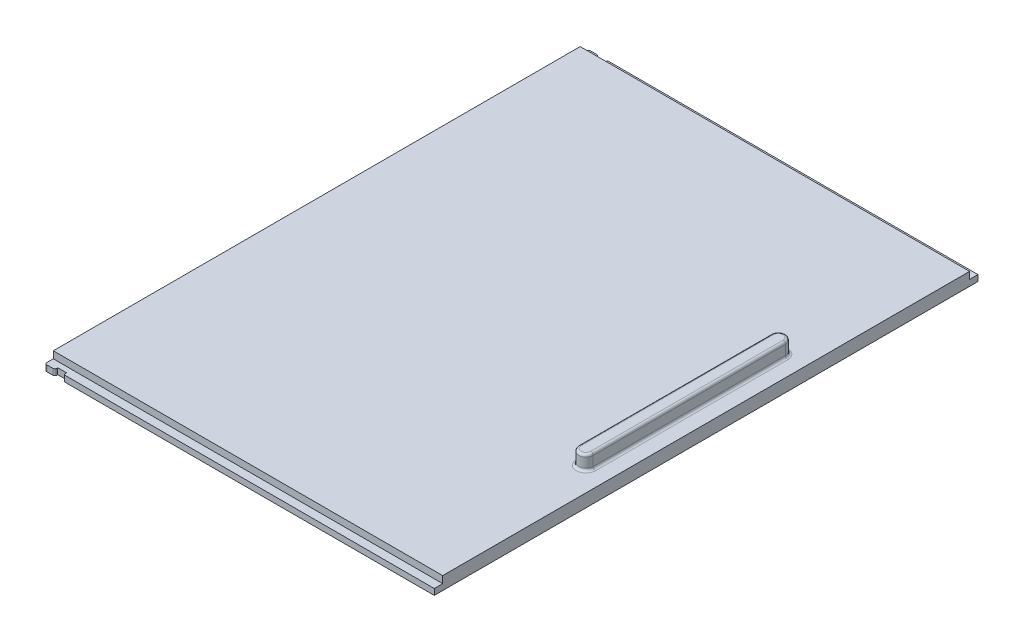
SolidWorks part; units mm, degrees
ref_plane "Front Plane" through (0, 0, 0) normal (0, 0, 1) x (1, 0, 0)
ref_plane "Top Plane" through (0, 0, 0) normal (0, 1, 0) x (1, 0, 0)
ref_plane "Right Plane" through (0, 0, 0) normal (1, 0, 0) x (0, 0, -1)
sketch "Sketch1" plane through (0, 0, 0) normal (0, 1, 0) x (1, 0, 0)
  line L1 (0, 0) -> (81, 0)
  line L2 (0, 0) -> (0, 116)
  line L3 (0, 116) -> (81, 116)
  line L4 (81, 0) -> (81, 116)
  dimension "D1" = 116
  dimension "D2" = 81
extrude "Boss-Extrude1" add sketch "Sketch1" along normal blind 3
sketch "Sketch2" plane through (81, 0, 0) normal (1, 0, 0) x (0, 0, -1)
  line L0 (0, 0) -> (116, 0) construction
  line L1 (0, 3) -> (3, 3)
  line L2 (0, 3) -> (0, 0)
  line L3 (0, 0) -> (1.25, 0)
  line L4 (3, 3) -> (3, 1.75)
  line L5 (3, 1.75) -> (1.25, 1.75)
  line L6 (1.25, 1.75) -> (1.25, 0)
  line L7 (114.75, 0) -> (116, 0)
  line L11 (58, 3) -> (58, 0) construction
  line L12 (0, 3) -> (116, 3) construction
  line L22 (116, 3) -> (113, 3)
  line L25 (114.75, 1.75) -> (113, 1.75)
  line L26 (113, 1.75) -> (113, 3)
  line L31 (114.75, 1.75) -> (114.75, 0)
  line L35 (116, 3) -> (116, 0)
  dimension "D1" = 3
  dimension "D2" = 1.25
  dimension "D3" = 1.25
  dimension "D4" = 3
extrude "Cut-Extrude2" cut sketch "Sketch2" against normal up to surface (81 mm away) up to face at (0, 1.5, -58)
sketch "Sketch4" plane through (81, 0, 0) normal (1, 0, 0) x (0, 0, -1)
  line L17 (58, 3) -> (58, 0) construction
  line L18 (3, 3) -> (113, 3) construction
  line L19 (1.25, 0) -> (114.75, 0) construction
  line L36 (3.2, 3) -> (3, 3)
  line L37 (3, 3) -> (3, 1.75)
  line L38 (3, 1.75) -> (3, 3) construction
  line L39 (1.45, 0) -> (1.45, 1.55)
  line L40 (1.45, 1.55) -> (3.2, 1.55)
  line L41 (3.2, 1.55) -> (3.2, 3)
  line L42 (1.45, 0) -> (1.45, 1.55)
  line L43 (1.45, 1.55) -> (3.2, 1.55)
  line L44 (3.2, 1.55) -> (3.2, 3)
  line L45 (3, 1.75) -> (1.25, 1.75)
  line L46 (1.25, 1.75) -> (1.25, 0)
  line L47 (1.25, 0) -> (1.45, 0)
  line L48 (114.75, 0) -> (114.55, 0)
  line L49 (114.75, 1.75) -> (114.75, 0)
  line L50 (113, 1.75) -> (114.75, 1.75)
  line L51 (112.8, 1.55) -> (112.8, 3)
  line L52 (114.55, 1.55) -> (112.8, 1.55)
  line L53 (114.55, 0) -> (114.55, 1.55)
  line L54 (113, 3) -> (113, 1.75)
  line L55 (112.8, 3) -> (113, 3)
  dimension "D1" = 0.2
extrude "Cut-Extrude3" cut sketch "Sketch4" against normal up to surface (81 mm away) up to face at (0, 1.625, -58)
sketch "Sketch6" plane through (0, 0, -1.45) normal (0, 0, 1) x (1, 0, 0)
  line L0 (3, 0.775) -> (0, 0.775) construction
  line L1 (0, 1.55) -> (0, 0) construction
  line L3 (2.075, 0) -> (3.925, 0)
  line L4 (2.075, 0) -> (2.075, 1.55)
  line L5 (2.075, 1.55) -> (3.925, 1.55)
  line L6 (3.925, 0) -> (3.925, 1.55)
  line L7 (2.075, 0) -> (3.925, 1.55) construction
  line L8 (2.075, 1.55) -> (3.925, 0) construction
  line L9 (0, 1.55) -> (81, 1.55) construction
  line L10 (0, 1.55) -> (81, 1.55) construction
  dimension "D1" = 3
  dimension "D3" = 1.85
  dimension "D4" = 0.775
extrude "Cut-Extrude5" cut sketch "Sketch6" against normal blind 0.6
fillet "Fillet6" radius 0.4 1 edges at (2.075, 0.775, -1.45)
chamfer "Chamfer2" distance 0.2 angle 45 1 edges at (3.925, 0.775, -1.45)
sketch "Sketch7" plane through (0, 0, -114.55) normal (0, 0, -1) x (-1, 0, 0)
  line L0 (-3, 0.775) -> (0, 0.775) construction
  line L3 (-2.075, 1.55) -> (-3.925, 1.55)
  line L4 (-2.075, 1.55) -> (-2.075, 0)
  line L5 (-2.075, 0) -> (-3.925, 0)
  line L6 (-3.925, 1.55) -> (-3.925, 0)
  line L7 (-2.075, 1.55) -> (-3.925, 0) construction
  line L8 (-2.075, 0) -> (-3.925, 1.55) construction
  line L9 (0, 0) -> (0, 1.55) construction
  line L10 (0, 1.55) -> (-81, 1.55) construction
  dimension "D1" = 3
  dimension "D3" = 1.85
  dimension "D4" = 0.775
extrude "Cut-Extrude6" cut sketch "Sketch7" against normal blind 0.6
fillet "Fillet7" radius 0.4 1 edges at (2.075, 0.775, -114.55)
chamfer "Chamfer3" distance 0.2 angle 45 1 edges at (3.925, 0.775, -114.55)
sketch "Sketch9" plane through (0, 3, 0) normal (0, 1, 0) x (1, 0, 0)
  line L0 (76, 38) -> (76, 78) construction
  line L1 (74.5, 38) -> (74.5, 78)
  line L2 (77.5, 38) -> (77.5, 78)
  line L3 (76, 78) -> (76, 112.8) construction
  line L5 (0, 112.8) -> (81, 112.8) construction
  line L14 (76, 38) -> (76, 3.2) construction
  line L15 (0, 3.2) -> (81, 3.2) construction
  line L16 (81, 3.2) -> (81, 112.8) construction
  arc A0 (74.5, 38) -> (77.5, 38) centre (76, 38) ccw
  arc A1 (77.5, 78) -> (74.5, 78) centre (76, 78) ccw
  point P2 (76, 58)
  dimension "D1" = 3
  dimension "D2" = 40
  dimension "D3" = 5
sketch "Sketch10" plane through (0, 0, 0) normal (0, -1, 0) x (-1, 0, 0)
  line L1 (0, 1.45) -> (-81, 1.45)
  line L2 (0, 1.45) -> (0, 114.55)
  line L3 (0, 114.55) -> (-81, 114.55)
  line L4 (-81, 1.45) -> (-81, 114.55)
extrude "Cut-Extrude7" cut sketch "Sketch10" against normal blind 0.2
fillet "Fillet8" radius 0.4 2 edges at (0, 0.875, -114.55) (0, 0.875, -1.45)
extrude "Boss-Extrude2" add sketch "Sketch9" along normal blind 3
fillet "Fillet10" radius 0.5 8 edges at (74.5, 3, -58) (76, 3, -79.5) (77.5, 3, -58) (74.5, 6, -58) (76, 6, -79.5) (77.5, 6, -58) (76, 6, -36.5) (76, 3, -36.5)
sketch "Sketch11" plane through (81, 0, 0) normal (1, 0, 0) x (0, 0, -1)
  line L0 (114.55, 1.55) -> (114.55, 0.2) construction
  line L1 (1.45, 0.2) -> (114.55, 0.2)
  line L2 (1.45, 0.2) -> (1.45, 0.3)
  line L3 (1.45, 0.3) -> (114.55, 0.3)
  line L4 (114.55, 0.2) -> (114.55, 0.3)
  point P5 (40.1416, 1.4147)
  point P6 (0, 0)
  point P7 (120.2267, 1.914)
  point P8 (114.55, 0.6324)
  dimension "D1" = 0.1
extrude "Cut-Extrude8" cut sketch "Sketch11" against normal up to surface (81 mm away) up to face at (0, 1.575, -58)
